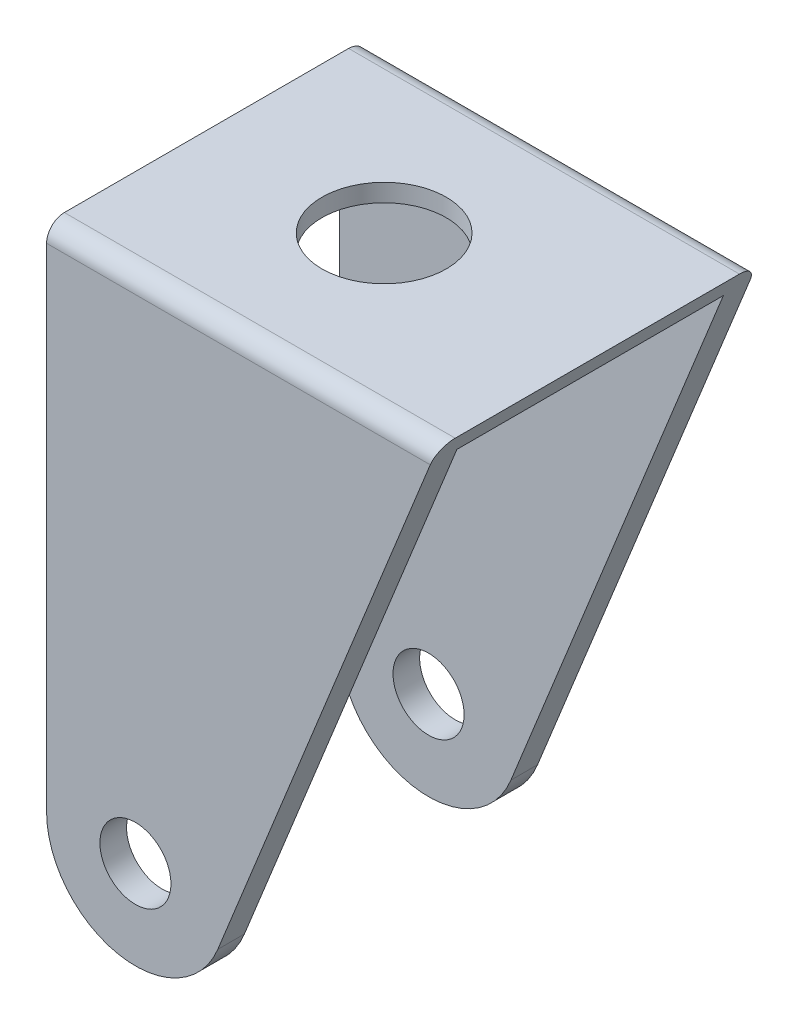
SolidWorks part; units mm, degrees
ref_plane "Front" through (0, 0, 0) normal (0, 0, 1) x (1, 0, 0)
ref_plane "Top" through (0, 0, 0) normal (0, 1, 0) x (1, 0, 0)
ref_plane "Right" through (0, 0, 0) normal (1, 0, 0) x (0, 0, -1)
sketch "草图1" plane through (0, 0, 0) normal (0, 0, 1) x (1, 0, 0)
  line L0 (-22, 34.9431) -> (22, 34.9431)
  line L1 (22, 34.9431) -> (-2.7282, -26.2612)
  line L2 (-22, -22.5152) -> (-22, 34.9431)
  arc A0 (-2.7282, -26.2612) -> (-22, -22.5152) centre (-12, -22.5152) cw
  circle A1 centre (-12, -22.5152) radius 4
  point P5 (0, 34.9431)
  dimension "D3" = 10
  dimension "D1" = 44
  dimension "D2" = 22
extrude "凸台-拉伸1" add sketch "草图1" along normal mid plane 36
sketch "草图2" plane through (0, 0, 0) normal (0, 0, 1) x (1, 0, 0)
  line L0 (-22, 32.9431) -> (21.1919, 32.9431)
  line L1 (22, 34.9431) -> (-22, 34.9431) construction
  line L3 (-22, 34.9431) -> (-22, -22.5152)
  line L4 (-2.7282, -26.2612) -> (22, 34.9431)
  line L5 (22, 34.9431) -> (-22, 34.9431)
  line L6 (-22, 32.9431) -> (-22, -22.5152)
  line L7 (-2.7282, -26.2612) -> (21.1919, 32.9431)
  arc A1 (-22, -22.5152) -> (-2.7282, -26.2612) centre (-12, -22.5152) ccw
  arc A2 (-22, -22.5152) -> (-2.7282, -26.2612) centre (-12, -22.5152) ccw
  dimension "D2" = 2
  dimension "D1" = 0
extrude "切除-拉伸1" cut sketch "草图2" against normal mid plane 30
hole_wizard "Ø14.0 (14) 直径孔1" positions "草图3" profile "草图4" hole size "Ø14.0" standard "GB" end condition up to next
sketch "草图3" plane through (0, 34.9431, 0) normal (0, 1, 0) x (1, 0, 0)
  line L0 (22, 18) -> (-22, 18) construction
  line L1 (-22, -18) -> (-22, 18) construction
  point P0 (-2, 0)
  dimension "D1" = 18
  dimension "D2" = 20
sketch "草图4" plane through (-2, 34.9431, 0) normal (1, 0, 0) x (0, 0, 1)
  line L0 (0, 0) -> (0, 2)
  line L1 (0, 2) -> (7, 2)
  line L2 (7, 2) -> (7, 0)
  line L5 (7, 0) -> (0, 0)
  line L11 (0, -6.35) -> (0, 107.95) construction
  dimension "通孔孔直径" = 14
  dimension "通孔孔深度" = 2
fillet "圆角1" radius 2 2 edges at (0, 34.9431, 18) (0, 34.9431, -18)
